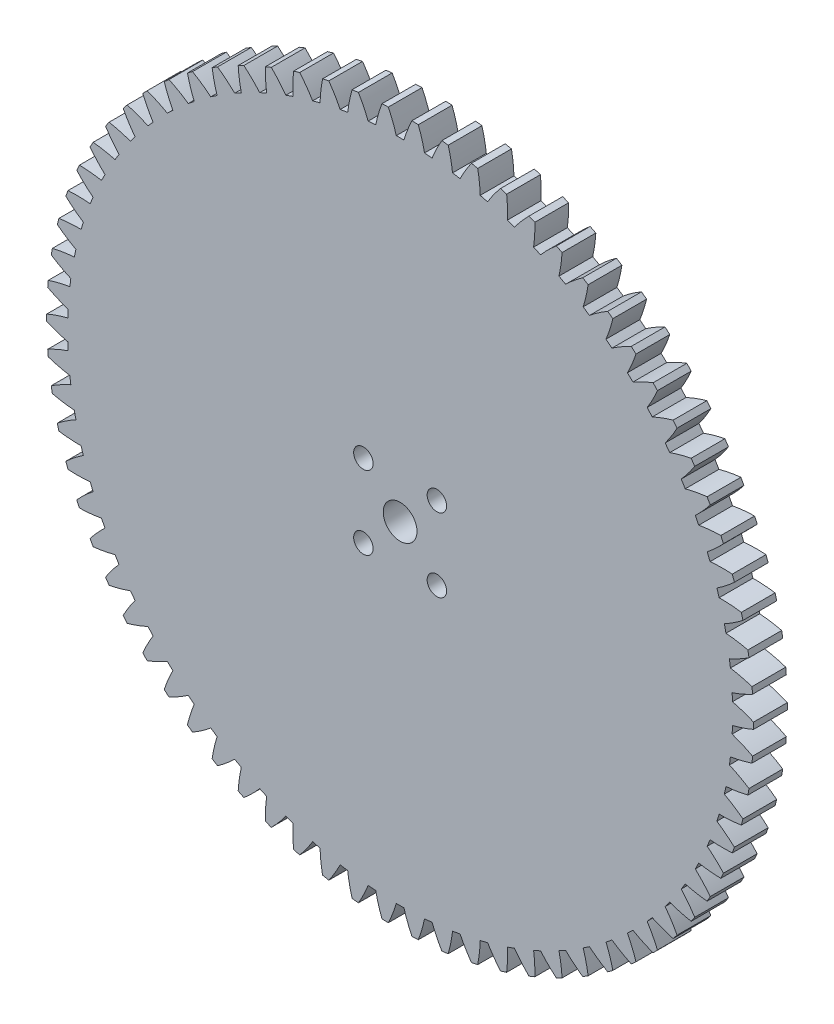
SolidWorks part; units mm, degrees
material "ABS"
ref_plane "Plan de face" through (0, 0, 0) normal (0, 0, 1) x (1, 0, 0)
ref_plane "Plan de dessus" through (0, 0, 0) normal (0, 1, 0) x (1, 0, 0)
ref_plane "Plan de droite" through (0, 0, 0) normal (1, 0, 0) x (0, 0, -1)
sketch "Esquisse1" plane through (0, 0, 0) normal (0, 0, 1) x (1, 0, 0)
  arc A592 (62.5315, -1.9382) -> (66.4973, -0.5986) centre (56.2528, 23.1893) ccw
  arc A593 (66.4973, -0.5986) -> (66.4973, 0.5986) centre (0, 0) ccw
  arc A594 (66.4973, 0.5986) -> (62.5315, 1.9382) centre (56.2528, -23.1893) ccw
  arc A595 (62.5315, 1.9382) -> (62.4706, 3.3719) centre (0, 0) ccw
  arc A596 (62.4706, 3.3719) -> (66.3085, 5.043) centre (54.0836, 27.8763) ccw
  arc A597 (66.3085, 5.043) -> (66.207, 6.2358) centre (0, 0) ccw
  arc A598 (66.207, 6.2358) -> (62.1418, 7.2342) centre (58.0168, -18.3352) ccw
  arc A599 (62.1418, 7.2342) -> (61.9596, 8.6576) centre (0, 0) ccw
  arc A600 (61.9596, 8.6576) -> (65.642, 10.6482) centre (51.5247, 32.3625) ccw
  arc A601 (65.642, 10.6482) -> (65.4396, 11.828) centre (0, 0) ccw
  arc A602 (65.4396, 11.828) -> (61.3045, 12.4782) centre (59.3627, -13.3489) ccw
  arc A603 (61.3045, 12.4782) -> (61.0021, 13.8809) centre (0, 0) ccw
  arc A604 (61.0021, 13.8809) -> (64.5025, 16.1766) centre (48.5945, 36.6155) ccw
  arc A605 (64.5025, 16.1766) -> (64.2008, 17.3351) centre (0, 0) ccw
  arc A606 (64.2008, 17.3351) -> (60.0254, 17.6322) centre (60.2809, -8.2665) ccw
  arc A607 (60.0254, 17.6322) -> (59.6052, 19.0043) centre (0, 0) ccw
  arc A608 (59.6052, 19.0043) -> (62.8982, 21.5885) centre (45.3143, 40.6047) ccw
  arc A609 (62.8982, 21.5885) -> (62.4994, 22.7173) centre (0, 0) ccw
  arc A610 (62.4994, 22.7173) -> (58.3138, 22.6592) centre (60.7648, -3.1246) ccw
  arc A611 (58.3138, 22.6592) -> (57.7788, 23.9907) centre (0, 0) ccw
  arc A612 (57.7788, 23.9907) -> (60.8408, 26.8449) centre (41.7075, 44.3014) ccw
  arc A613 (60.8408, 26.8449) -> (60.3477, 27.9357) centre (0, 0) ccw
  arc A614 (60.3477, 27.9357) -> (56.1821, 27.5229) centre (60.8109, 2.0399) ccw
  arc A615 (56.1821, 27.5229) -> (55.5361, 28.8042) centre (0, 0) ccw
  arc A616 (55.5361, 28.8042) -> (58.345, 31.9079) centre (37.8002, 47.6788) ccw
  arc A617 (58.345, 31.9079) -> (57.7612, 32.9529) centre (0, 0) ccw
  arc A618 (57.7612, 32.9529) -> (53.6456, 32.1883) centre (60.4188, 7.1897) ccw
  arc A619 (53.6456, 32.1883) -> (52.8933, 33.4103) centre (0, 0) ccw
  arc A620 (52.8933, 33.4103) -> (55.4288, 36.7409) centre (33.6206, 50.7127) ccw
  arc A621 (55.4288, 36.7409) -> (54.7585, 37.7327) centre (0, 0) ccw
  arc A622 (54.7585, 37.7327) -> (50.7226, 36.6218) centre (59.5914, 12.2876) ccw
  arc A623 (50.7226, 36.6218) -> (49.8693, 37.7756) centre (0, 0) ccw
  arc A624 (49.8693, 37.7756) -> (52.1133, 41.3092) centre (29.1988, 53.3813) ccw
  arc A625 (52.1133, 41.3092) -> (51.3613, 42.2406) centre (0, 0) ccw
  arc A626 (51.3613, 42.2406) -> (47.4341, 40.7915) centre (58.3347, 17.2971) ccw
  arc A627 (47.4341, 40.7915) -> (46.4861, 41.8687) centre (0, 0) ccw
  arc A628 (46.4861, 41.8687) -> (48.4223, 45.5799) centre (24.5665, 55.6652) ccw
  arc A629 (48.4223, 45.5799) -> (47.594, 46.4442) centre (0, 0) ccw
  arc A630 (47.594, 46.4442) -> (43.8039, 44.6672) centre (56.6577, 22.1819) ccw
  arc A631 (43.8039, 44.6672) -> (42.7679, 45.6601) centre (0, 0) ccw
  arc A632 (42.7679, 45.6601) -> (44.3824, 49.5222) centre (19.7573, 57.548) ccw
  arc A633 (44.3824, 49.5222) -> (43.4838, 50.3131) centre (0, 0) ccw
  arc A634 (43.4838, 50.3131) -> (39.858, 48.2211) centre (54.5724, 26.9069) ccw
  arc A635 (39.858, 48.2211) -> (38.7416, 49.1226) centre (0, 0) ccw
  arc A636 (38.7416, 49.1226) -> (40.0227, 53.1077) centre (14.8057, 59.0162) ccw
  arc A637 (40.0227, 53.1077) -> (39.0603, 53.8196) centre (0, 0) ccw
  arc A638 (39.0603, 53.8196) -> (35.625, 51.4276) centre (52.0939, 31.438) ccw
  arc A639 (35.625, 51.4276) -> (34.4361, 52.2312) centre (0, 0) ccw
  arc A640 (34.4361, 52.2312) -> (35.3747, 56.3106) centre (9.7474, 60.0592) ccw
  arc A641 (35.3747, 56.3106) -> (34.3553, 56.9382) centre (0, 0) ccw
  arc A642 (34.3553, 56.9382) -> (31.1353, 54.2636) centre (49.2401, 35.7426) ccw
  arc A643 (31.1353, 54.2636) -> (29.8825, 54.9634) centre (0, 0) ccw
  arc A644 (29.8825, 54.9634) -> (30.4718, 59.1077) centre (4.6189, 60.6695) ccw
  arc A645 (30.4718, 59.1077) -> (29.4029, 59.6466) centre (0, 0) ccw
  arc A646 (29.4029, 59.6466) -> (26.4213, 56.7085) centre (46.0316, 39.7897) ccw
  arc A647 (26.4213, 56.7085) -> (25.1137, 57.2996) centre (0, 0) ccw
  arc A648 (25.1137, 57.2996) -> (25.3493, 61.4789) centre (-0.5428, 60.8427) ccw
  arc A649 (25.3493, 61.4789) -> (24.2386, 61.9253) centre (0, 0) ccw
  arc A650 (24.2386, 61.9253) -> (21.5169, 58.7449) centre (42.4913, 43.5501) ccw
  arc A651 (21.5169, 58.7449) -> (20.1639, 59.223) centre (0, 0) ccw
  arc A652 (20.1639, 59.223) -> (20.0442, 63.4072) centre (-5.7007, 60.5775) ccw
  arc A653 (20.0442, 63.4072) -> (18.8996, 63.7578) centre (0, 0) ccw
  arc A654 (18.8996, 63.7578) -> (16.4574, 60.3581) centre (38.6449, 46.9968) ccw
  arc A655 (16.4574, 60.3581) -> (15.0688, 60.7196) centre (0, 0) ccw
  arc A656 (15.0688, 60.7196) -> (14.5947, 64.8787) centre (-10.8175, 59.8758) ccw
  arc A657 (14.5947, 64.8787) -> (13.4245, 65.1309) centre (0, 0) ccw
  arc A658 (13.4245, 65.1309) -> (11.2794, 61.5363) centre (34.5201, 50.1048) ccw
  arc A659 (11.2794, 61.5363) -> (9.8651, 61.7788) centre (0, 0) ccw
  arc A660 (9.8651, 61.7788) -> (9.04, 65.8827) centre (-15.8563, 58.7427) ccw
  arc A661 (9.04, 65.8827) -> (7.8526, 66.0347) centre (0, 0) ccw
  arc A662 (7.8526, 66.0347) -> (6.0201, 62.2712) centre (30.1466, 52.8518) ccw
  arc A663 (6.0201, 62.2712) -> (4.5903, 62.3929) centre (0, 0) ccw
  arc A664 (4.5903, 62.3929) -> (3.4202, 66.412) centre (-20.781, 57.1863) ccw
  arc A665 (3.4202, 66.412) -> (2.2242, 66.4628) centre (0, 0) ccw
  arc A666 (2.2242, 66.4628) -> (0.7175, 62.5574) centre (25.5558, 55.218) ccw
  arc A667 (0.7175, 62.5574) -> (-0.7175, 62.5574) centre (0, 0) ccw
  arc A668 (-0.7175, 62.5574) -> (-2.2242, 66.4628) centre (-25.5558, 55.218) ccw
  arc A669 (-2.2242, 66.4628) -> (-3.4202, 66.412) centre (0, 0) ccw
  arc A670 (-3.4202, 66.412) -> (-4.5903, 62.3929) centre (20.781, 57.1863) ccw
  arc A671 (-4.5903, 62.3929) -> (-6.0201, 62.2712) centre (0, 0) ccw
  arc A672 (-6.0201, 62.2712) -> (-7.8526, 66.0347) centre (-30.1466, 52.8518) ccw
  arc A673 (-7.8526, 66.0347) -> (-9.04, 65.8827) centre (0, 0) ccw
  arc A674 (-9.04, 65.8827) -> (-9.8651, 61.7788) centre (15.8563, 58.7427) ccw
  arc A675 (-9.8651, 61.7788) -> (-11.2794, 61.5363) centre (0, 0) ccw
  arc A676 (-11.2794, 61.5363) -> (-13.4245, 65.1309) centre (-34.5201, 50.1048) ccw
  arc A677 (-13.4245, 65.1309) -> (-14.5947, 64.8787) centre (0, 0) ccw
  arc A678 (-14.5947, 64.8787) -> (-15.0688, 60.7196) centre (10.8175, 59.8758) ccw
  arc A679 (-15.0688, 60.7196) -> (-16.4574, 60.3581) centre (0, 0) ccw
  arc A680 (-16.4574, 60.3581) -> (-18.8996, 63.7578) centre (-38.6449, 46.9968) ccw
  arc A681 (-18.8996, 63.7578) -> (-20.0442, 63.4072) centre (0, 0) ccw
  arc A682 (-20.0442, 63.4072) -> (-20.1639, 59.223) centre (5.7007, 60.5775) ccw
  arc A683 (-20.1639, 59.223) -> (-21.5169, 58.7449) centre (0, 0) ccw
  arc A684 (-21.5169, 58.7449) -> (-24.2386, 61.9253) centre (-42.4913, 43.5501) ccw
  arc A685 (-24.2386, 61.9253) -> (-25.3493, 61.4789) centre (0, 0) ccw
  arc A686 (-25.3493, 61.4789) -> (-25.1137, 57.2996) centre (0.5428, 60.8427) ccw
  arc A687 (-25.1137, 57.2996) -> (-26.4213, 56.7085) centre (0, 0) ccw
  arc A688 (-26.4213, 56.7085) -> (-29.4029, 59.6466) centre (-46.0316, 39.7897) ccw
  arc A689 (-29.4029, 59.6466) -> (-30.4718, 59.1077) centre (0, 0) ccw
  arc A690 (-30.4718, 59.1077) -> (-29.8825, 54.9634) centre (-4.6189, 60.6695) ccw
  arc A691 (-29.8825, 54.9634) -> (-31.1353, 54.2636) centre (0, 0) ccw
  arc A692 (-31.1353, 54.2636) -> (-34.3553, 56.9382) centre (-49.2401, 35.7426) ccw
  arc A693 (-34.3553, 56.9382) -> (-35.3747, 56.3106) centre (0, 0) ccw
  arc A694 (-35.3747, 56.3106) -> (-34.4361, 52.2312) centre (-9.7474, 60.0592) ccw
  arc A695 (-34.4361, 52.2312) -> (-35.625, 51.4276) centre (0, 0) ccw
  arc A696 (-35.625, 51.4276) -> (-39.0603, 53.8196) centre (-52.0939, 31.438) ccw
  arc A697 (-39.0603, 53.8196) -> (-40.0227, 53.1077) centre (0, 0) ccw
  arc A698 (-40.0227, 53.1077) -> (-38.7416, 49.1226) centre (-14.8057, 59.0162) ccw
  arc A699 (-38.7416, 49.1226) -> (-39.858, 48.2211) centre (0, 0) ccw
  arc A700 (-39.858, 48.2211) -> (-43.4838, 50.3131) centre (-54.5724, 26.9069) ccw
  arc A701 (-43.4838, 50.3131) -> (-44.3824, 49.5222) centre (0, 0) ccw
  arc A702 (-44.3824, 49.5222) -> (-42.7679, 45.6601) centre (-19.7573, 57.548) ccw
  arc A703 (-42.7679, 45.6601) -> (-43.8039, 44.6672) centre (0, 0) ccw
  arc A704 (-43.8039, 44.6672) -> (-47.594, 46.4442) centre (-56.6577, 22.1819) ccw
  arc A705 (-47.594, 46.4442) -> (-48.4223, 45.5799) centre (0, 0) ccw
  arc A706 (-48.4223, 45.5799) -> (-46.4861, 41.8687) centre (-24.5665, 55.6652) ccw
  arc A707 (-46.4861, 41.8687) -> (-47.4341, 40.7915) centre (0, 0) ccw
  arc A708 (-47.4341, 40.7915) -> (-51.3613, 42.2406) centre (-58.3347, 17.2971) ccw
  arc A709 (-51.3613, 42.2406) -> (-52.1133, 41.3092) centre (0, 0) ccw
  arc A710 (-52.1133, 41.3092) -> (-49.8693, 37.7756) centre (-29.1988, 53.3813) ccw
  arc A711 (-49.8693, 37.7756) -> (-50.7226, 36.6218) centre (0, 0) ccw
  arc A712 (-50.7226, 36.6218) -> (-54.7585, 37.7327) centre (-59.5914, 12.2876) ccw
  arc A713 (-54.7585, 37.7327) -> (-55.4288, 36.7409) centre (0, 0) ccw
  arc A714 (-55.4288, 36.7409) -> (-52.8933, 33.4103) centre (-33.6206, 50.7127) ccw
  arc A715 (-52.8933, 33.4103) -> (-53.6456, 32.1883) centre (0, 0) ccw
  arc A716 (-53.6456, 32.1883) -> (-57.7612, 32.9529) centre (-60.4188, 7.1897) ccw
  arc A717 (-57.7612, 32.9529) -> (-58.345, 31.9079) centre (0, 0) ccw
  arc A718 (-58.345, 31.9079) -> (-55.5361, 28.8042) centre (-37.8002, 47.6788) ccw
  arc A719 (-55.5361, 28.8042) -> (-56.1821, 27.5229) centre (0, 0) ccw
  arc A720 (-56.1821, 27.5229) -> (-60.3477, 27.9357) centre (-60.8109, 2.0399) ccw
  arc A721 (-60.3477, 27.9357) -> (-60.8408, 26.8449) centre (0, 0) ccw
  arc A722 (-60.8408, 26.8449) -> (-57.7788, 23.9907) centre (-41.7075, 44.3014) ccw
  arc A723 (-57.7788, 23.9907) -> (-58.3138, 22.6592) centre (0, 0) ccw
  arc A724 (-58.3138, 22.6592) -> (-62.4994, 22.7173) centre (-60.7648, -3.1246) ccw
  arc A725 (-62.4994, 22.7173) -> (-62.8982, 21.5885) centre (0, 0) ccw
  arc A726 (-62.8982, 21.5885) -> (-59.6052, 19.0043) centre (-45.3143, 40.6047) ccw
  arc A727 (-59.6052, 19.0043) -> (-60.0254, 17.6322) centre (0, 0) ccw
  arc A728 (-60.0254, 17.6322) -> (-64.2008, 17.3351) centre (-60.2809, -8.2665) ccw
  arc A729 (-64.2008, 17.3351) -> (-64.5025, 16.1766) centre (0, 0) ccw
  arc A730 (-64.5025, 16.1766) -> (-61.0021, 13.8809) centre (-48.5945, 36.6155) ccw
  arc A731 (-61.0021, 13.8809) -> (-61.3045, 12.4782) centre (0, 0) ccw
  arc A732 (-61.3045, 12.4782) -> (-65.4396, 11.828) centre (-59.3627, -13.3489) ccw
  arc A733 (-65.4396, 11.828) -> (-65.642, 10.6482) centre (0, 0) ccw
  arc A734 (-65.642, 10.6482) -> (-61.9596, 8.6576) centre (-51.5247, 32.3625) ccw
  arc A735 (-61.9596, 8.6576) -> (-62.1418, 7.2342) centre (0, 0) ccw
  arc A736 (-62.1418, 7.2342) -> (-66.207, 6.2358) centre (-58.0168, -18.3352) ccw
  arc A737 (-66.207, 6.2358) -> (-66.3085, 5.043) centre (0, 0) ccw
  arc A738 (-66.3085, 5.043) -> (-62.4706, 3.3719) centre (-54.0836, 27.8763) ccw
  arc A739 (-62.4706, 3.3719) -> (-62.5315, 1.9382) centre (0, 0) ccw
  arc A740 (-62.5315, 1.9382) -> (-66.4973, 0.5986) centre (-56.2528, -23.1893) ccw
  arc A741 (-66.4973, 0.5986) -> (-66.4973, -0.5986) centre (0, 0) ccw
  arc A742 (-66.4973, -0.5986) -> (-62.5315, -1.9382) centre (-56.2528, 23.1893) ccw
  arc A743 (-62.5315, -1.9382) -> (-62.4706, -3.3719) centre (0, 0) ccw
  arc A744 (-62.4706, -3.3719) -> (-66.3085, -5.043) centre (-54.0836, -27.8763) ccw
  arc A745 (-66.3085, -5.043) -> (-66.207, -6.2358) centre (0, 0) ccw
  arc A746 (-66.207, -6.2358) -> (-62.1418, -7.2342) centre (-58.0168, 18.3352) ccw
  arc A747 (-62.1418, -7.2342) -> (-61.9596, -8.6576) centre (0, 0) ccw
  arc A748 (-61.9596, -8.6576) -> (-65.642, -10.6482) centre (-51.5247, -32.3625) ccw
  arc A749 (-65.642, -10.6482) -> (-65.4396, -11.828) centre (0, 0) ccw
  arc A750 (-65.4396, -11.828) -> (-61.3045, -12.4782) centre (-59.3627, 13.3489) ccw
  arc A751 (-61.3045, -12.4782) -> (-61.0021, -13.8809) centre (0, 0) ccw
  arc A752 (-61.0021, -13.8809) -> (-64.5025, -16.1766) centre (-48.5945, -36.6155) ccw
  arc A753 (-64.5025, -16.1766) -> (-64.2008, -17.3351) centre (0, 0) ccw
  arc A754 (-64.2008, -17.3351) -> (-60.0254, -17.6322) centre (-60.2809, 8.2665) ccw
  arc A755 (-60.0254, -17.6322) -> (-59.6052, -19.0043) centre (0, 0) ccw
  arc A756 (-59.6052, -19.0043) -> (-62.8982, -21.5885) centre (-45.3143, -40.6047) ccw
  arc A757 (-62.8982, -21.5885) -> (-62.4994, -22.7173) centre (0, 0) ccw
  arc A758 (-62.4994, -22.7173) -> (-58.3138, -22.6592) centre (-60.7648, 3.1246) ccw
  arc A759 (-58.3138, -22.6592) -> (-57.7788, -23.9907) centre (0, 0) ccw
  arc A760 (-57.7788, -23.9907) -> (-60.8408, -26.8449) centre (-41.7075, -44.3014) ccw
  arc A761 (-60.8408, -26.8449) -> (-60.3477, -27.9357) centre (0, 0) ccw
  arc A762 (-60.3477, -27.9357) -> (-56.1821, -27.5229) centre (-60.8109, -2.0399) ccw
  arc A763 (-56.1821, -27.5229) -> (-55.5361, -28.8042) centre (0, 0) ccw
  arc A764 (-55.5361, -28.8042) -> (-58.345, -31.9079) centre (-37.8002, -47.6788) ccw
  arc A765 (-58.345, -31.9079) -> (-57.7612, -32.9529) centre (0, 0) ccw
  arc A766 (-57.7612, -32.9529) -> (-53.6456, -32.1883) centre (-60.4188, -7.1897) ccw
  arc A767 (-53.6456, -32.1883) -> (-52.8933, -33.4103) centre (0, 0) ccw
  arc A768 (-52.8933, -33.4103) -> (-55.4288, -36.7409) centre (-33.6206, -50.7127) ccw
  arc A769 (-55.4288, -36.7409) -> (-54.7585, -37.7327) centre (0, 0) ccw
  arc A770 (-54.7585, -37.7327) -> (-50.7226, -36.6218) centre (-59.5914, -12.2876) ccw
  arc A771 (-50.7226, -36.6218) -> (-49.8693, -37.7756) centre (0, 0) ccw
  arc A772 (-49.8693, -37.7756) -> (-52.1133, -41.3092) centre (-29.1988, -53.3813) ccw
  arc A773 (-52.1133, -41.3092) -> (-51.3613, -42.2406) centre (0, 0) ccw
  arc A774 (-51.3613, -42.2406) -> (-47.4341, -40.7915) centre (-58.3347, -17.2971) ccw
  arc A775 (-47.4341, -40.7915) -> (-46.4861, -41.8687) centre (0, 0) ccw
  arc A776 (-46.4861, -41.8687) -> (-48.4223, -45.5799) centre (-24.5665, -55.6652) ccw
  arc A777 (-48.4223, -45.5799) -> (-47.594, -46.4442) centre (0, 0) ccw
  arc A778 (-47.594, -46.4442) -> (-43.8039, -44.6672) centre (-56.6577, -22.1819) ccw
  arc A779 (-43.8039, -44.6672) -> (-42.7679, -45.6601) centre (0, 0) ccw
  arc A780 (-42.7679, -45.6601) -> (-44.3824, -49.5222) centre (-19.7573, -57.548) ccw
  arc A781 (-44.3824, -49.5222) -> (-43.4838, -50.3131) centre (0, 0) ccw
  arc A782 (-43.4838, -50.3131) -> (-39.858, -48.2211) centre (-54.5724, -26.9069) ccw
  arc A783 (-39.858, -48.2211) -> (-38.7416, -49.1226) centre (0, 0) ccw
  arc A784 (-38.7416, -49.1226) -> (-40.0227, -53.1077) centre (-14.8057, -59.0162) ccw
  arc A785 (-40.0227, -53.1077) -> (-39.0603, -53.8196) centre (0, 0) ccw
  arc A786 (-39.0603, -53.8196) -> (-35.625, -51.4276) centre (-52.0939, -31.438) ccw
  arc A787 (-35.625, -51.4276) -> (-34.4361, -52.2312) centre (0, 0) ccw
  arc A788 (-34.4361, -52.2312) -> (-35.3747, -56.3106) centre (-9.7474, -60.0592) ccw
  arc A789 (-35.3747, -56.3106) -> (-34.3553, -56.9382) centre (0, 0) ccw
  arc A790 (-34.3553, -56.9382) -> (-31.1353, -54.2636) centre (-49.2401, -35.7426) ccw
  arc A791 (-31.1353, -54.2636) -> (-29.8825, -54.9634) centre (0, 0) ccw
  arc A792 (-29.8825, -54.9634) -> (-30.4718, -59.1077) centre (-4.6189, -60.6695) ccw
  arc A793 (-30.4718, -59.1077) -> (-29.4029, -59.6466) centre (0, 0) ccw
  arc A794 (-29.4029, -59.6466) -> (-26.4213, -56.7085) centre (-46.0316, -39.7897) ccw
  arc A795 (-26.4213, -56.7085) -> (-25.1137, -57.2996) centre (0, 0) ccw
  arc A796 (-25.1137, -57.2996) -> (-25.3493, -61.4789) centre (0.5428, -60.8427) ccw
  arc A797 (-25.3493, -61.4789) -> (-24.2386, -61.9253) centre (0, 0) ccw
  arc A798 (-24.2386, -61.9253) -> (-21.5169, -58.7449) centre (-42.4913, -43.5501) ccw
  arc A799 (-21.5169, -58.7449) -> (-20.1639, -59.223) centre (0, 0) ccw
  arc A800 (-20.1639, -59.223) -> (-20.0442, -63.4072) centre (5.7007, -60.5775) ccw
  arc A801 (-20.0442, -63.4072) -> (-18.8996, -63.7578) centre (0, 0) ccw
  arc A802 (-18.8996, -63.7578) -> (-16.4574, -60.3581) centre (-38.6449, -46.9968) ccw
  arc A803 (-16.4574, -60.3581) -> (-15.0688, -60.7196) centre (0, 0) ccw
  arc A804 (-15.0688, -60.7196) -> (-14.5947, -64.8787) centre (10.8175, -59.8758) ccw
  arc A805 (-14.5947, -64.8787) -> (-13.4245, -65.1309) centre (0, 0) ccw
  arc A806 (-13.4245, -65.1309) -> (-11.2794, -61.5363) centre (-34.5201, -50.1048) ccw
  arc A807 (-11.2794, -61.5363) -> (-9.8651, -61.7788) centre (0, 0) ccw
  arc A808 (-9.8651, -61.7788) -> (-9.04, -65.8827) centre (15.8563, -58.7427) ccw
  arc A809 (-9.04, -65.8827) -> (-7.8526, -66.0347) centre (0, 0) ccw
  arc A810 (-7.8526, -66.0347) -> (-6.0201, -62.2712) centre (-30.1466, -52.8518) ccw
  arc A811 (-6.0201, -62.2712) -> (-4.5903, -62.3929) centre (0, 0) ccw
  arc A812 (-4.5903, -62.3929) -> (-3.4202, -66.412) centre (20.781, -57.1863) ccw
  arc A813 (-3.4202, -66.412) -> (-2.2242, -66.4628) centre (0, 0) ccw
  arc A814 (-2.2242, -66.4628) -> (-0.7175, -62.5574) centre (-25.5558, -55.218) ccw
  arc A815 (-0.7175, -62.5574) -> (0.7175, -62.5574) centre (0, 0) ccw
  arc A816 (0.7175, -62.5574) -> (2.2242, -66.4628) centre (25.5558, -55.218) ccw
  arc A817 (2.2242, -66.4628) -> (3.4202, -66.412) centre (0, 0) ccw
  arc A818 (3.4202, -66.412) -> (4.5903, -62.3929) centre (-20.781, -57.1863) ccw
  arc A819 (4.5903, -62.3929) -> (6.0201, -62.2712) centre (0, 0) ccw
  arc A820 (6.0201, -62.2712) -> (7.8526, -66.0347) centre (30.1466, -52.8518) ccw
  arc A821 (7.8526, -66.0347) -> (9.04, -65.8827) centre (0, 0) ccw
  arc A822 (9.04, -65.8827) -> (9.8651, -61.7788) centre (-15.8563, -58.7427) ccw
  arc A823 (9.8651, -61.7788) -> (11.2794, -61.5363) centre (0, 0) ccw
  arc A824 (11.2794, -61.5363) -> (13.4245, -65.1309) centre (34.5201, -50.1048) ccw
  arc A825 (13.4245, -65.1309) -> (14.5947, -64.8787) centre (0, 0) ccw
  arc A826 (14.5947, -64.8787) -> (15.0688, -60.7196) centre (-10.8175, -59.8758) ccw
  arc A827 (15.0688, -60.7196) -> (16.4574, -60.3581) centre (0, 0) ccw
  arc A828 (16.4574, -60.3581) -> (18.8996, -63.7578) centre (38.6449, -46.9968) ccw
  arc A829 (18.8996, -63.7578) -> (20.0442, -63.4072) centre (0, 0) ccw
  arc A830 (20.0442, -63.4072) -> (20.1639, -59.223) centre (-5.7007, -60.5775) ccw
  arc A831 (20.1639, -59.223) -> (21.5169, -58.7449) centre (0, 0) ccw
  arc A832 (21.5169, -58.7449) -> (24.2386, -61.9253) centre (42.4913, -43.5501) ccw
  arc A833 (24.2386, -61.9253) -> (25.3493, -61.4789) centre (0, 0) ccw
  arc A834 (25.3493, -61.4789) -> (25.1137, -57.2996) centre (-0.5428, -60.8427) ccw
  arc A835 (25.1137, -57.2996) -> (26.4213, -56.7085) centre (0, 0) ccw
  arc A836 (26.4213, -56.7085) -> (29.4029, -59.6466) centre (46.0316, -39.7897) ccw
  arc A837 (29.4029, -59.6466) -> (30.4718, -59.1077) centre (0, 0) ccw
  arc A838 (30.4718, -59.1077) -> (29.8825, -54.9634) centre (4.6189, -60.6695) ccw
  arc A839 (29.8825, -54.9634) -> (31.1353, -54.2636) centre (0, 0) ccw
  arc A840 (31.1353, -54.2636) -> (34.3553, -56.9382) centre (49.2401, -35.7426) ccw
  arc A841 (34.3553, -56.9382) -> (35.3747, -56.3106) centre (0, 0) ccw
  arc A842 (35.3747, -56.3106) -> (34.4361, -52.2312) centre (9.7474, -60.0592) ccw
  arc A843 (34.4361, -52.2312) -> (35.625, -51.4276) centre (0, 0) ccw
  arc A844 (35.625, -51.4276) -> (39.0603, -53.8196) centre (52.0939, -31.438) ccw
  arc A845 (39.0603, -53.8196) -> (40.0227, -53.1077) centre (0, 0) ccw
  arc A846 (40.0227, -53.1077) -> (38.7416, -49.1226) centre (14.8057, -59.0162) ccw
  arc A847 (38.7416, -49.1226) -> (39.858, -48.2211) centre (0, 0) ccw
  arc A848 (39.858, -48.2211) -> (43.4838, -50.3131) centre (54.5724, -26.9069) ccw
  arc A849 (43.4838, -50.3131) -> (44.3824, -49.5222) centre (0, 0) ccw
  arc A850 (44.3824, -49.5222) -> (42.7679, -45.6601) centre (19.7573, -57.548) ccw
  arc A851 (42.7679, -45.6601) -> (43.8039, -44.6672) centre (0, 0) ccw
  arc A852 (43.8039, -44.6672) -> (47.594, -46.4442) centre (56.6577, -22.1819) ccw
  arc A853 (47.594, -46.4442) -> (48.4223, -45.5799) centre (0, 0) ccw
  arc A854 (48.4223, -45.5799) -> (46.4861, -41.8687) centre (24.5665, -55.6652) ccw
  arc A855 (46.4861, -41.8687) -> (47.4341, -40.7915) centre (0, 0) ccw
  arc A856 (47.4341, -40.7915) -> (51.3613, -42.2406) centre (58.3347, -17.2971) ccw
  arc A857 (51.3613, -42.2406) -> (52.1133, -41.3092) centre (0, 0) ccw
  arc A858 (52.1133, -41.3092) -> (49.8693, -37.7756) centre (29.1988, -53.3813) ccw
  arc A859 (49.8693, -37.7756) -> (50.7226, -36.6218) centre (0, 0) ccw
  arc A860 (50.7226, -36.6218) -> (54.7585, -37.7327) centre (59.5914, -12.2876) ccw
  arc A861 (54.7585, -37.7327) -> (55.4288, -36.7409) centre (0, 0) ccw
  arc A862 (55.4288, -36.7409) -> (52.8933, -33.4103) centre (33.6206, -50.7127) ccw
  arc A863 (52.8933, -33.4103) -> (53.6456, -32.1883) centre (0, 0) ccw
  arc A864 (53.6456, -32.1883) -> (57.7612, -32.9529) centre (60.4188, -7.1897) ccw
  arc A865 (57.7612, -32.9529) -> (58.345, -31.9079) centre (0, 0) ccw
  arc A866 (58.345, -31.9079) -> (55.5361, -28.8042) centre (37.8002, -47.6788) ccw
  arc A867 (55.5361, -28.8042) -> (56.1821, -27.5229) centre (0, 0) ccw
  arc A868 (56.1821, -27.5229) -> (60.3477, -27.9357) centre (60.8109, -2.0399) ccw
  arc A869 (60.3477, -27.9357) -> (60.8408, -26.8449) centre (0, 0) ccw
  arc A870 (60.8408, -26.8449) -> (57.7788, -23.9907) centre (41.7075, -44.3014) ccw
  arc A871 (57.7788, -23.9907) -> (58.3138, -22.6592) centre (0, 0) ccw
  arc A872 (58.3138, -22.6592) -> (62.4994, -22.7173) centre (60.7648, 3.1246) ccw
  arc A873 (62.4994, -22.7173) -> (62.8982, -21.5885) centre (0, 0) ccw
  arc A874 (62.8982, -21.5885) -> (59.6052, -19.0043) centre (45.3143, -40.6047) ccw
  arc A875 (59.6052, -19.0043) -> (60.0254, -17.6322) centre (0, 0) ccw
  arc A876 (60.0254, -17.6322) -> (64.2008, -17.3351) centre (60.2809, 8.2665) ccw
  arc A877 (64.2008, -17.3351) -> (64.5025, -16.1766) centre (0, 0) ccw
  arc A878 (64.5025, -16.1766) -> (61.0021, -13.8809) centre (48.5945, -36.6155) ccw
  arc A879 (61.0021, -13.8809) -> (61.3045, -12.4782) centre (0, 0) ccw
  arc A880 (61.3045, -12.4782) -> (65.4396, -11.828) centre (59.3627, 13.3489) ccw
  arc A881 (65.4396, -11.828) -> (65.642, -10.6482) centre (0, 0) ccw
  arc A882 (65.642, -10.6482) -> (61.9596, -8.6576) centre (51.5247, -32.3625) ccw
  arc A883 (61.9596, -8.6576) -> (62.1418, -7.2342) centre (0, 0) ccw
  arc A884 (62.1418, -7.2342) -> (66.207, -6.2358) centre (58.0168, 18.3352) ccw
  arc A885 (66.207, -6.2358) -> (66.3085, -5.043) centre (0, 0) ccw
  arc A886 (66.3085, -5.043) -> (62.4706, -3.3719) centre (54.0836, -27.8763) ccw
  arc A887 (62.4706, -3.3719) -> (62.5315, -1.9382) centre (0, 0) ccw
extrude "Boss.-Extru.1" add sketch "Esquisse1" along normal mid plane 6.35
sketch "Esquisse2" plane through (0, 0, 3.175) normal (0, 0, 1) x (1, 0, 0)
  circle A0 centre (0, 0) radius 3.175
  circle A1 centre (6.9148, 6.9148) radius 1.83
  circle A2 centre (6.9148, -6.9148) radius 1.83
  circle A3 centre (-6.9148, -6.9148) radius 1.83
  circle A4 centre (-6.9148, 6.9148) radius 1.83
  point P15 (0, 0)
  dimension "D1" = 3.66
  dimension "D2" = 6.35
  dimension "D3" = 4
extrude "Enlèv. mat.-Extru.1" cut sketch "Esquisse2" against normal up to next
